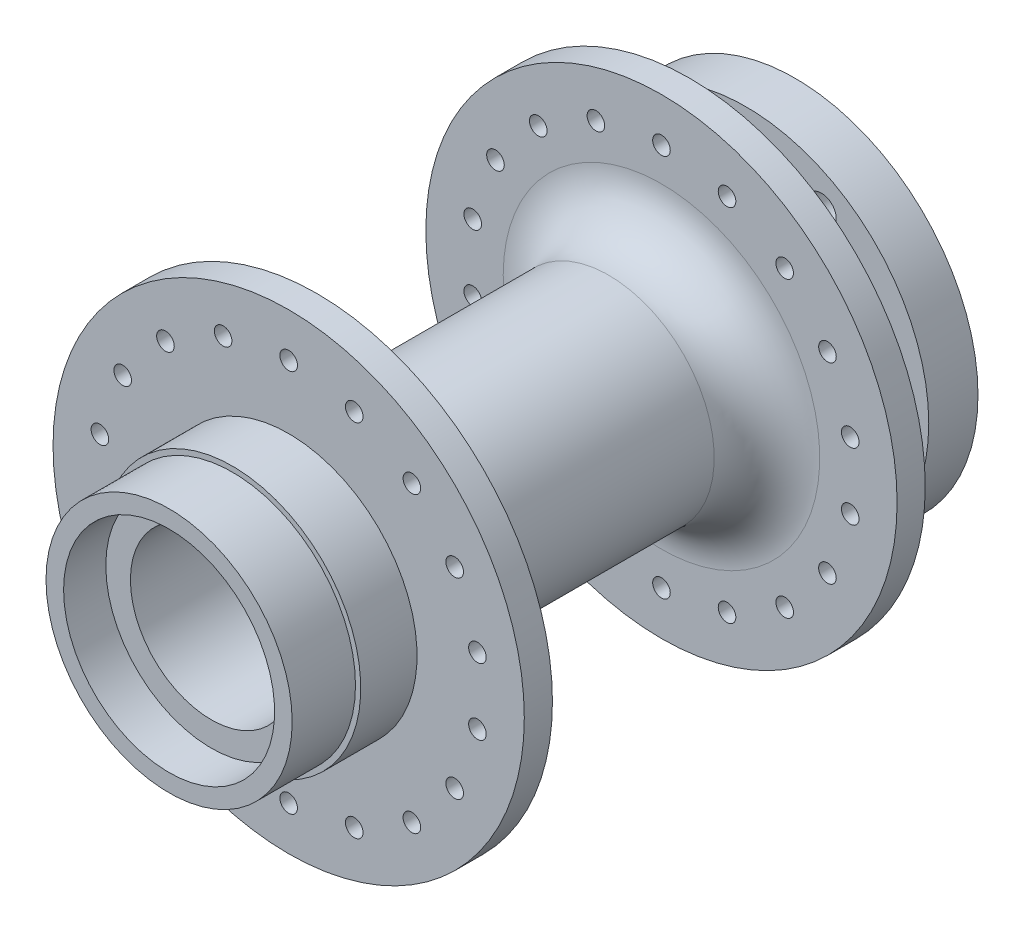
SolidWorks part; units mm, degrees
ref_plane "Front Plane" through (0, 0, 0) normal (0, 0, 1) x (1, 0, 0)
ref_plane "Top Plane" through (0, 0, 0) normal (0, 1, 0) x (1, 0, 0)
ref_plane "Right Plane" through (0, 0, 0) normal (1, 0, 0) x (0, 0, -1)
sketch "Sketch1" plane through (0, 0, 0) normal (0, 1, 0) x (1, 0, 0)
  line L0 (0, 29.0975) -> (0, -27.9135) construction
sketch "Sketch2" plane through (0, 0, 0) normal (0, 1, 0) x (1, 0, 0)
  line L0 (15, 46) -> (16, 46)
  line L1 (0, 200029.0975) -> (0, -200027.9135) construction
  line L2 (16, 46) -> (16, 43)
  line L3 (16, 43) -> (26, 43)
  line L4 (26, 43) -> (26, 35.9999)
  line L5 (26, 35.9999) -> (18.25, 35.9999)
  line L6 (18.25, 35.9999) -> (18.25, 27.9999)
  line L7 (18.25, 27.9999) -> (33.5, 27.9999)
  line L8 (33.5, 27.9999) -> (33.5, 23.9999)
  line L9 (33.5, 23.9999) -> (15, 23.9999)
  line L10 (15, 23.9999) -> (15, -25.0001)
  line L11 (15, -25.0001) -> (33.5, -25.0001)
  line L12 (33.5, -25.0001) -> (33.5, -29.0001)
  line L13 (33.5, -29.0001) -> (18.25, -29.0001)
  line L15 (17.5, -46) -> (15, -46)
  line L17 (11.5, 0) -> (0, 0) construction
  line L18 (15, -46) -> (15, -40)
  line L19 (15, -40) -> (11.5, -40)
  line L20 (11.5, -40) -> (11.5, 40)
  line L21 (11.5, 40) -> (15, 40)
  line L22 (15, 40) -> (15, 46)
  line L23 (17.5, -46) -> (17.5, -37.0001)
  line L24 (17.5, -37.0001) -> (18.25, -37.0001)
  line L25 (18.25, -37.0001) -> (18.25, -29.0001)
  dimension "D1" = 4
  dimension "D2" = 15
  dimension "D3" = 33.5
  dimension "D4" = 16
  dimension "D5" = 26
  dimension "D6" = 18.25
  dimension "D7" = 8
  dimension "D8" = 92
  dimension "D9" = 15
  dimension "D10" = 3
  dimension "D11" = 7.0001
  dimension "D12" = 57
  dimension "D13" = 6
  dimension "D14" = 3.5
  dimension "D15" = 17.5
revolve "Revolve1" add sketch "Sketch2" angle 360 about L0
fillet "Fillet1" radius 7.5 2 edges at (-15, 0, 25.0001) (-15, 0, -23.9999)
fillet "Fillet2" radius 2.5 1 edges at (-18.25, 0, -35.9999)
sketch "Sketch3" plane through (0, 0, 0) normal (0, 0, 1) x (1, 0, 0)
  line L0 (0, 0) -> (0, 26) construction
  line L1 (0, 26) -> (0, 27.25) construction
  line L2 (0, 27.25) -> (0, 28.5) construction
  line L3 (0, 28.5) -> (0, 33.5) construction
  circle A0 centre (0, 27.25) radius 1.25
  circle A1 centre (0, 0) radius 33.5 construction
  circle A2 centre (9.32, 25.6066) radius 1.25
  circle A3 centre (17.516, 20.8747) radius 1.25
  circle A4 centre (23.5992, 13.625) radius 1.25
  circle A5 centre (26.836, 4.7319) radius 1.25
  circle A6 centre (26.836, -4.7319) radius 1.25
  circle A7 centre (23.5992, -13.625) radius 1.25
  circle A8 centre (17.516, -20.8747) radius 1.25
  circle A9 centre (9.32, -25.6066) radius 1.25
  circle A10 centre (0, -27.25) radius 1.25
  circle A11 centre (-9.32, -25.6066) radius 1.25
  circle A12 centre (-17.516, -20.8747) radius 1.25
  circle A13 centre (-23.5992, -13.625) radius 1.25
  circle A14 centre (-26.836, -4.7319) radius 1.25
  circle A15 centre (-26.836, 4.7319) radius 1.25
  circle A16 centre (-23.5992, 13.625) radius 1.25
  circle A17 centre (-17.516, 20.8747) radius 1.25
  circle A18 centre (-9.32, 25.6066) radius 1.25
  point P46 (0, 0)
  dimension "D1" = 2.5
  dimension "D2" = 5
  dimension "D3" = 18
extrude "Cut-Extrude1" cut sketch "Sketch3" against normal through all both and the other way through all
sketch "Sketch4" plane through (0, 0, -43) normal (0, 0, -1) x (-1, 0, 0)
  line L0 (0, 0) -> (9.5, 16.4545) construction
  line L1 (9.5, 16.4545) -> (10.75, 18.6195) construction
  line L2 (10.75, 18.6195) -> (12, 20.7846) construction
  line L3 (12, 20.7846) -> (13, 22.5167) construction
  line L4 (0, 0) -> (0, 26) construction
  circle A0 centre (10.75, 18.6195) radius 2.5 construction
  circle A1 centre (0, 0) radius 26 construction
  circle A2 centre (21.5, 0) radius 2.5 construction
  circle A3 centre (10.75, -18.6195) radius 2.5 construction
  circle A4 centre (-10.75, -18.6195) radius 2.5 construction
  circle A5 centre (-21.5, 0) radius 2.5 construction
  circle A6 centre (-10.75, 18.6195) radius 2.5 construction
  point P25 (0, 0)
  dimension "D1" = 5
  dimension "D3" = 30
  dimension "D4" = 2
  dimension "D2" = 6
hole_wizard "M5x0.8 Tapped Hole1" positions "Sketch5" profile "Sketch6" tap size "M5x0.8" standard "ANSI Metric"
sketch "Sketch5" plane through (0, 0, -43) normal (0, 0, -1) x (-1, 0, 0)
  point P0 (-10.75, 18.6195)
  point P3 (10.75, 18.6195)
  point P6 (21.5, 0)
  point P9 (10.75, -18.6195)
  point P12 (-10.75, -18.6195)
  point P15 (-21.5, 0)
sketch "Sketch6" plane through (10.75, 18.6195, -43) normal (1, 0, 0) x (0, 1, 0)
  line L0 (0, 0) -> (0, 7.0001)
  line L1 (0, 7.0001) -> (2.1, 7.0001)
  line L2 (2.1, 7.0001) -> (2.1, 0)
  line L5 (2.1, 0) -> (0, 0)
  line L11 (0, -6.35) -> (0, 107.95) construction
  dimension "Thru Tap Drill Dia." = 4.2
  dimension "Thru Tap Drill Depth" = 7.0001
cosmetic thread "Hole Thread1" parameters "D2"=5
cosmetic thread "Hole Thread2" parameters "D2"=5
cosmetic thread "Hole Thread3" parameters "D2"=5
cosmetic thread "Hole Thread4" parameters "D2"=5
cosmetic thread "Hole Thread5" parameters "D2"=5
cosmetic thread "Hole Thread6" parameters "D2"=5
